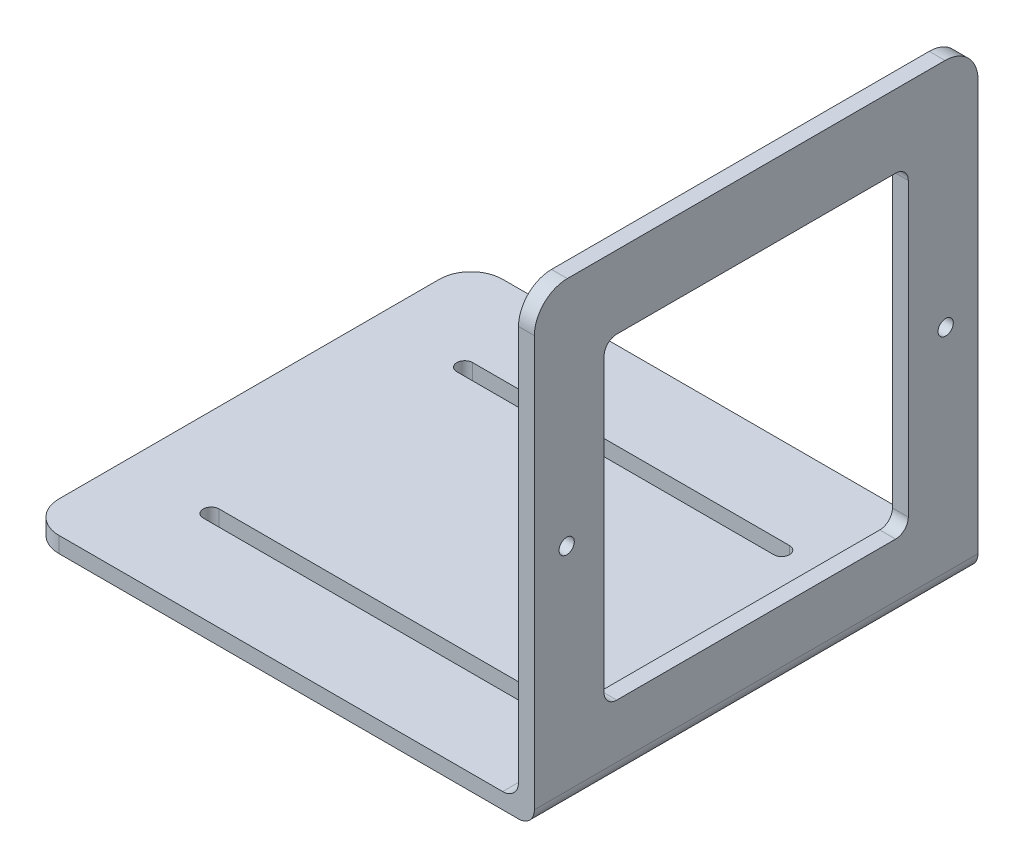
SolidWorks part; units mm, degrees
ref_plane "Front Plane" through (0, 0, 0) normal (0, 0, 1) x (1, 0, 0)
ref_plane "Top Plane" through (0, 0, 0) normal (0, 1, 0) x (1, 0, 0)
ref_plane "Right Plane" through (0, 0, 0) normal (1, 0, 0) x (0, 0, -1)
sketch "Sketch2" plane through (0, 0, 0) normal (0, 1, 0) x (1, 0, 0)
  line L0 (0, 0) -> (177.8, 0) construction
  line L2 (0, -44.45) -> (101.6, -44.45)
  line L3 (0, -44.45) -> (0, 44.45)
  line L4 (0, 44.45) -> (101.6, 44.45)
  line L5 (101.6, -44.45) -> (101.6, 44.45)
  point P8 (0, 0)
  dimension "D2" = 177.8
  dimension "D3" = 101.6
extrude "Boss-Extrude1" add sketch "Sketch2" along normal blind 3.175
sketch "Sketch3" plane through (0, 3.175, 0) normal (0, 1, 0) x (1, 0, 0)
  line L1 (101.6, 44.45) -> (98.425, 44.45)
  line L2 (101.6, 44.45) -> (101.6, -44.45)
  line L3 (101.6, -44.45) -> (98.425, -44.45)
  line L4 (98.425, 44.45) -> (98.425, -44.45)
  dimension "D1" = 3.175
extrude "Boss-Extrude2" add sketch "Sketch3" along normal blind 88.9
sketch "Sketch5" plane through (101.6, 0, 0) normal (1, 0, 0) x (0, 0, -1)
  line L0 (0, 0) -> (0, 45.72) construction
  line L1 (-37.973, 45.72) -> (37.973, 45.72) construction
  line L3 (-25.273, 62.459) -> (25.273, 62.459) construction
  line L4 (30.48, 13.97) -> (-30.48, 13.97)
  line L5 (30.48, 13.97) -> (30.48, 77.47)
  line L6 (30.48, 77.47) -> (-30.48, 77.47)
  line L7 (-30.48, 13.97) -> (-30.48, 77.47)
  line L8 (30.48, 13.97) -> (-30.48, 77.47) construction
  line L9 (30.48, 77.47) -> (-30.48, 13.97) construction
  line L10 (-44.45, 0) -> (44.45, 0) construction
  circle A0 centre (-37.973, 45.72) radius 1.524
  circle A1 centre (37.973, 45.72) radius 1.524
  point P13 (0, 62.459)
  point P23 (0, 0)
  dimension "D3" = 3.048
  dimension "D1" = 75.946
  dimension "D2" = 45.72
  dimension "D4" = 60.96
  dimension "D5" = 63.5
  dimension "D6" = 50.546
extrude "Cut-Extrude2" cut sketch "Sketch5" against normal through all
fillet "Fillet1" radius 2.54 4 edges at (100.0125, 13.97, -30.48) (100.0125, 77.47, -30.48) (100.0125, 13.97, 30.48) (100.0125, 77.47, 30.48)
fillet "Fillet2" radius 6.604 2 edges at (100.0125, 92.075, 44.45) (100.0125, 92.075, -44.45)
fillet "Fillet3" radius 3.175 2 edges at (98.425, 3.175, 0) (101.6, 0, 0)
fillet "Fillet4" radius 6.35 2 edges at (0, 1.5875, -44.45) (0, 1.5875, 44.45)
sketch "Sketch6" plane through (0, 3.175, 0) normal (0, 1, 0) x (1, 0, 0)
  line L0 (0, 0) -> (94.7543, 0) construction
  line L1 (17.7957, 25.4) -> (81.2957, 25.4) construction
  line L2 (17.7957, 26.9875) -> (81.2957, 26.9875)
  line L3 (17.7957, 23.8125) -> (81.2957, 23.8125)
  line L4 (49.5457, 25.4) -> (49.5457, 0) construction
  line L5 (17.7957, -25.4) -> (81.2957, -25.4) construction
  line L6 (17.7957, -26.9875) -> (81.2957, -26.9875)
  line L7 (17.7957, -23.8125) -> (81.2957, -23.8125)
  arc A0 (17.7957, 26.9875) -> (17.7957, 23.8125) centre (17.7957, 25.4) ccw
  arc A1 (81.2957, 23.8125) -> (81.2957, 26.9875) centre (81.2957, 25.4) ccw
  arc A2 (17.7957, -26.9875) -> (17.7957, -23.8125) centre (17.7957, -25.4) cw
  arc A3 (81.2957, -23.8125) -> (81.2957, -26.9875) centre (81.2957, -25.4) cw
  point P5 (49.5457, 25.4)
  point P14 (49.5457, -25.4)
  dimension "D1" = 1.5875
  dimension "D2" = 63.5
  dimension "D3" = 25.4
extrude "Cut-Extrude3" cut sketch "Sketch6" against normal through all
